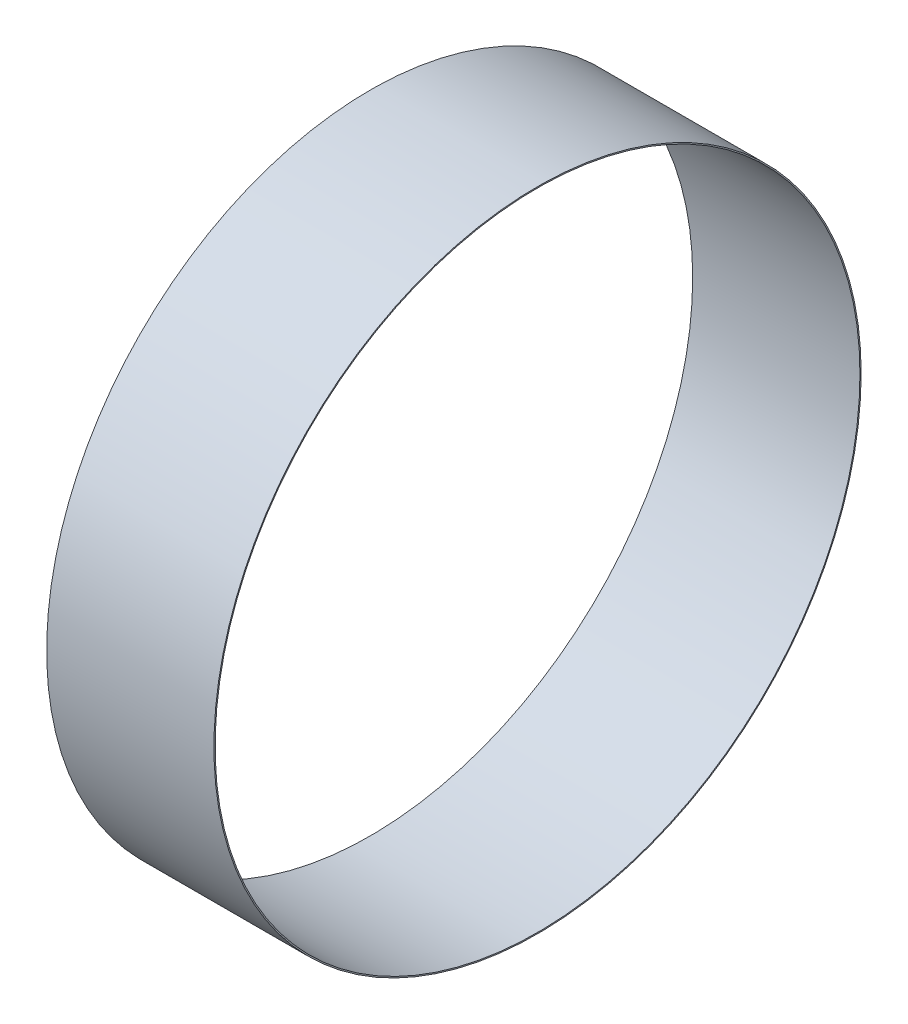
SolidWorks part; units mm, degrees
ref_plane "Front Plane" through (0, 0, 0) normal (0, 0, 1) x (1, 0, 0)
ref_plane "Top Plane" through (0, 0, 0) normal (0, 1, 0) x (1, 0, 0)
ref_plane "Right Plane" through (0, 0, 0) normal (1, 0, 0) x (0, 0, -1)
sketch "Sketch1" plane through (0, 0, 0) normal (1, 0, 0) x (0, 0, -1)
  circle A0 centre (0, 0) radius 800
  circle A1 centre (0, 0) radius 803
  dimension "D1" = 1606
  dimension "D2" = 1600
extrude "Boss-Extrude1" add sketch "Sketch1" along normal blind 415
